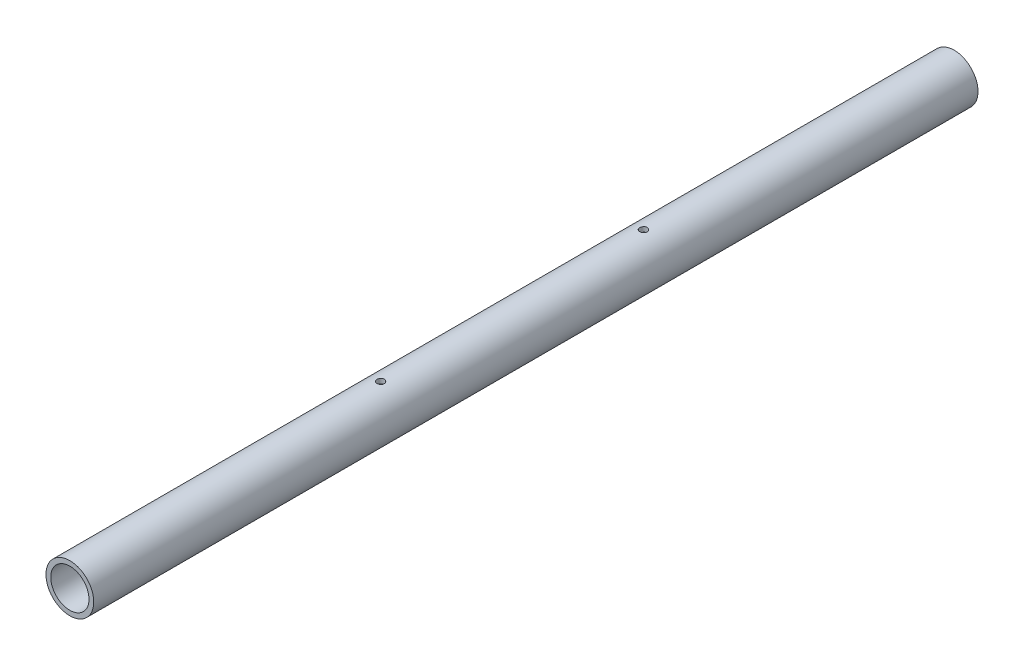
SolidWorks part; units mm, degrees
material "Thornel Mat VMA"
ref_plane "前视基准面" through (0, 0, 0) normal (0, 0, 1) x (1, 0, 0)
ref_plane "上视基准面" through (0, 0, 0) normal (0, 1, 0) x (1, 0, 0)
ref_plane "右视基准面" through (0, 0, 0) normal (1, 0, 0) x (0, 0, -1)
other "Configuration Table"
sketch "草图1" plane through (0, 0, 0) normal (0, 0, 1) x (1, 0, 0)
  circle A0 centre (0, 0) radius 10
  circle A1 centre (0, 0) radius 8
  dimension "D1" = 20
  dimension "D2" = 16
extrude "凸台-拉伸1" add sketch "草图1" along normal blind 370
sketch "草图2" plane through (0, 0, 0) normal (0, 1, 0) x (1, 0, 0)
  line L0 (0, -370) -> (0, 0) construction
  line L1 (-10, -370) -> (10, -370) construction
  line L2 (0, -185) -> (0, -130) construction
  line L3 (0, -185) -> (0, -240) construction
  circle A0 centre (0, -130) radius 1.55
  circle A1 centre (0, -240) radius 1.55
  dimension "D3" = 3.1
  dimension "D4" = 3.1
  dimension "D1" = 55
  dimension "D2" = 55
  dimension "D5" = 130
  dimension "D6" = 130
extrude "切除-拉伸1" cut sketch "草图2" against normal through all and the other way through all
